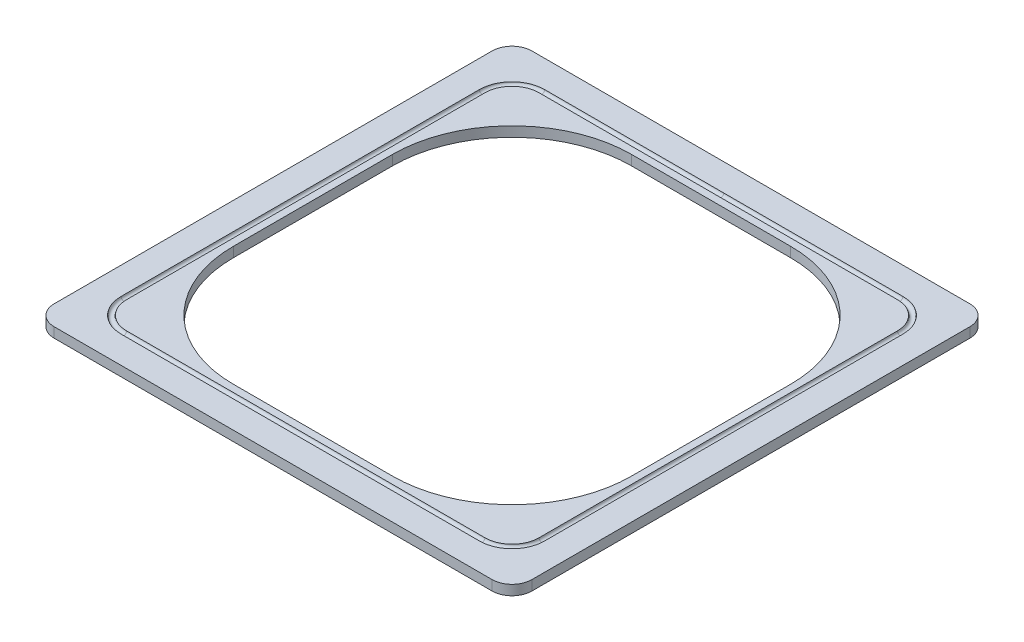
SolidWorks part; units mm, degrees
ref_plane "Front Plane" through (0, 0, 0) normal (0, 0, 1) x (1, 0, 0)
ref_plane "Top Plane" through (0, 0, 0) normal (0, 1, 0) x (1, 0, 0)
ref_plane "Right Plane" through (0, 0, 0) normal (1, 0, 0) x (0, 0, -1)
sketch "Sketch1" plane through (0, 0, 0) normal (0, 1, 0) x (1, 0, 0)
  line L0 (-127, 127) -> (127, 127)
  line L1 (-152.4, -152.4) -> (152.4, -152.4)
  line L2 (-152.4, -152.4) -> (-152.4, 152.4)
  line L3 (-152.4, 152.4) -> (152.4, 152.4)
  line L4 (152.4, -152.4) -> (152.4, 152.4)
  line L5 (-152.4, -152.4) -> (152.4, 152.4) construction
  line L6 (-152.4, 152.4) -> (152.4, -152.4) construction
  line L7 (127, -127) -> (127, 127)
  line L8 (-127, -127) -> (127, -127)
  line L9 (-127, -127) -> (-127, 127)
  line L10 (-146.05, -146.05) -> (-146.05, 146.05) construction
  line L11 (-146.05, 146.05) -> (146.05, 146.05) construction
  line L12 (146.05, -146.05) -> (146.05, 146.05) construction
  line L13 (-146.05, -146.05) -> (146.05, -146.05) construction
  point P0 (0, 0)
  dimension "D1" = 304.8
  dimension "D2" = 304.8
  dimension "D3" = 25.4
  dimension "D4" = 6.35
extrude "Boss-Extrude1" add sketch "Sketch1" along normal blind 6.35
fillet "Fillet1" radius 76.2 4 edges at (127, 3.175, 127) (-127, 3.175, 127) (-127, 3.175, -127) (127, 3.175, -127)
fillet "Fillet2" radius 12.7 4 edges at (-152.4, 3.175, 152.4) (-152.4, 3.175, -152.4) (152.4, 3.175, -152.4) (152.4, 3.175, 152.4)
sketch "Sketch3" plane through (0, 6.35, 0) normal (0, 1, 0) x (1, 0, 0)
  line L1 (114.3, -133.35) -> (-114.3, -133.35)
  line L2 (133.35, -114.3) -> (133.35, 114.3)
  line L3 (114.3, 133.35) -> (-114.3, 133.35)
  line L4 (-133.35, -114.3) -> (-133.35, 114.3)
  arc A0 (133.35, 114.3) -> (114.3, 133.35) centre (114.3, 114.3) ccw
  arc A1 (133.35, -114.3) -> (114.3, -133.35) centre (114.3, -114.3) cw
  arc A2 (-114.3, -133.35) -> (-133.35, -114.3) centre (-114.3, -114.3) cw
  arc A3 (-114.3, 133.35) -> (-133.35, 114.3) centre (-114.3, 114.3) ccw
  point P0 (0, 0)
  dimension "D3" = 19.05
  dimension "D2" = 228.6
  dimension "D1" = 228.6
  dimension "D4" = 133.35
  dimension "D5" = 133.35
sketch "Sketch4" plane through (0, 0, 0) normal (1, 0, 0) x (0, 0, -1)
  circle A0 centre (133.35, 6.35) radius 1.7653
  dimension "D1" = 3.5306
sweep "Cut-Sweep1" cut profiles "Sketch4" path "Sketch3"
